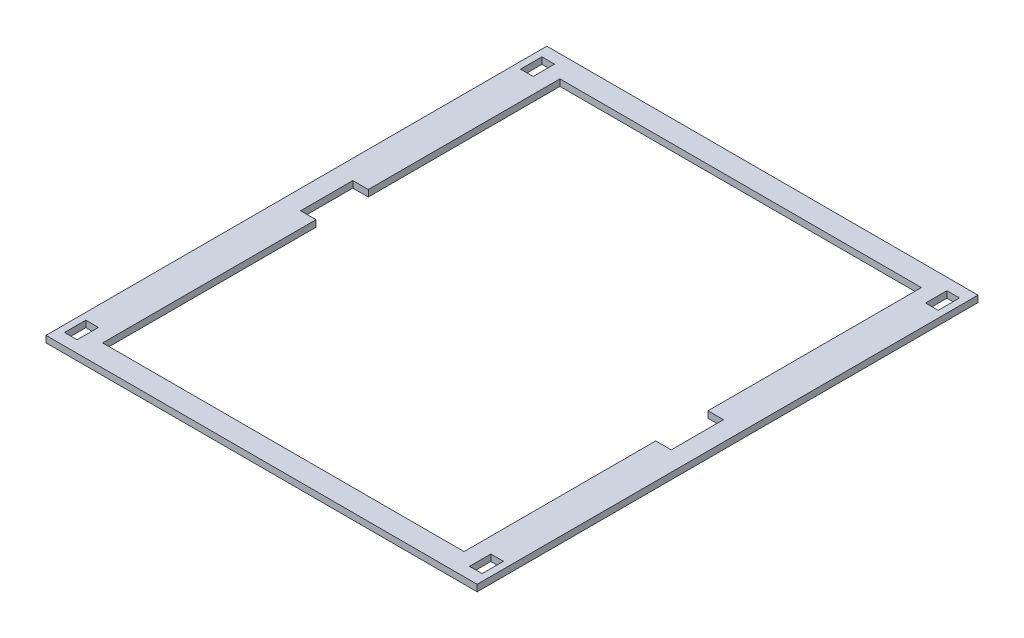
SolidWorks part; units mm, degrees
ref_plane "Front Plane" through (0, 0, 0) normal (0, 0, 1) x (1, 0, 0)
ref_plane "Top Plane" through (0, 0, 0) normal (0, 1, 0) x (1, 0, 0)
ref_plane "Right Plane" through (0, 0, 0) normal (1, 0, 0) x (0, 0, -1)
sketch "Sketch1" plane through (0, 0, 0) normal (0, 1, 0) x (1, 0, 0)
  line L1 (0, 0) -> (198, 0)
  line L2 (0, 0) -> (0, 230)
  line L3 (0, 230) -> (198, 230)
  line L4 (198, 0) -> (198, 230)
  line L5 (16, 220) -> (182, 220)
  line L6 (16, 220) -> (16, 10)
  line L7 (16, 10) -> (182, 10)
  line L8 (182, 220) -> (182, 10)
  dimension "D1" = 230
  dimension "D2" = 198
  dimension "D3" = 16
  dimension "D4" = 16
  dimension "D5" = 10
  dimension "D6" = 10
  dimension "D7" = 166
extrude "Boss-Extrude1" add sketch "Sketch1" along normal blind 3
sketch "Sketch2" plane through (0, 3, 0) normal (0, 1, 0) x (1, 0, 0)
  line L0 (99, 230) -> (99, 0) construction
  line L1 (3.1026, 224.6205) -> (8.9026, 224.6205)
  line L2 (3.1026, 224.6205) -> (3.1026, 214.8205)
  line L3 (3.1026, 214.8205) -> (8.9026, 214.8205)
  line L4 (8.9026, 224.6205) -> (8.9026, 214.8205)
  line L5 (198, 230) -> (0, 230) construction
  line L6 (0, 0) -> (198, 0) construction
  line L7 (0, 115) -> (198, 115) construction
  line L8 (0, 230) -> (0, 0) construction
  line L9 (198, 0) -> (198, 230) construction
  line L10 (194.8974, 214.8205) -> (189.0974, 214.8205)
  line L11 (189.0974, 224.6205) -> (189.0974, 214.8205)
  line L12 (194.8974, 224.6205) -> (189.0974, 224.6205)
  line L13 (194.8974, 224.6205) -> (194.8974, 214.8205)
  line L14 (194.8974, 5.3795) -> (194.8974, 15.1795)
  line L15 (194.8974, 5.3795) -> (189.0974, 5.3795)
  line L16 (189.0974, 5.3795) -> (189.0974, 15.1795)
  line L17 (194.8974, 15.1795) -> (189.0974, 15.1795)
  line L18 (3.1026, 15.1795) -> (8.9026, 15.1795)
  line L19 (8.9026, 5.3795) -> (8.9026, 15.1795)
  line L20 (3.1026, 5.3795) -> (8.9026, 5.3795)
  line L21 (3.1026, 5.3795) -> (3.1026, 15.1795)
  line L22 (182, 220) -> (182, 122)
  line L23 (16, 220) -> (16, 10) construction
  line L24 (16, 10) -> (16, 108)
  line L25 (182, 10) -> (182, 220) construction
  line L26 (16, 220) -> (16, 132)
  line L27 (182, 10) -> (182, 98)
  line L29 (16, 132) -> (8.9026, 132)
  line L30 (16, 132) -> (16, 108)
  line L31 (16, 108) -> (8.9026, 108)
  line L32 (8.9026, 132) -> (8.9026, 108)
  line L33 (182, 122) -> (189.0974, 122)
  line L34 (182, 122) -> (182, 98)
  line L35 (182, 98) -> (189.0974, 98)
  line L36 (189.0974, 122) -> (189.0974, 98)
  line M7 (16, 10) -> (16, 220)
  line M9 (182, 220) -> (182, 10)
  dimension "D1" = 5.8
  dimension "D2" = 9.8
  dimension "D3" = 98
  dimension "D4" = 98
  dimension "D5" = 88
  dimension "D6" = 88
extrude "Cut-Extrude1" cut sketch "Sketch2" against normal blind 3 contours L29 L32 L31 M7 | L14 L17 L16 L15 | L36 L33 L35 M9 | L13 L12 L11 L10 | L1 L4 L3 L2 | L18 L19 L20 L21
